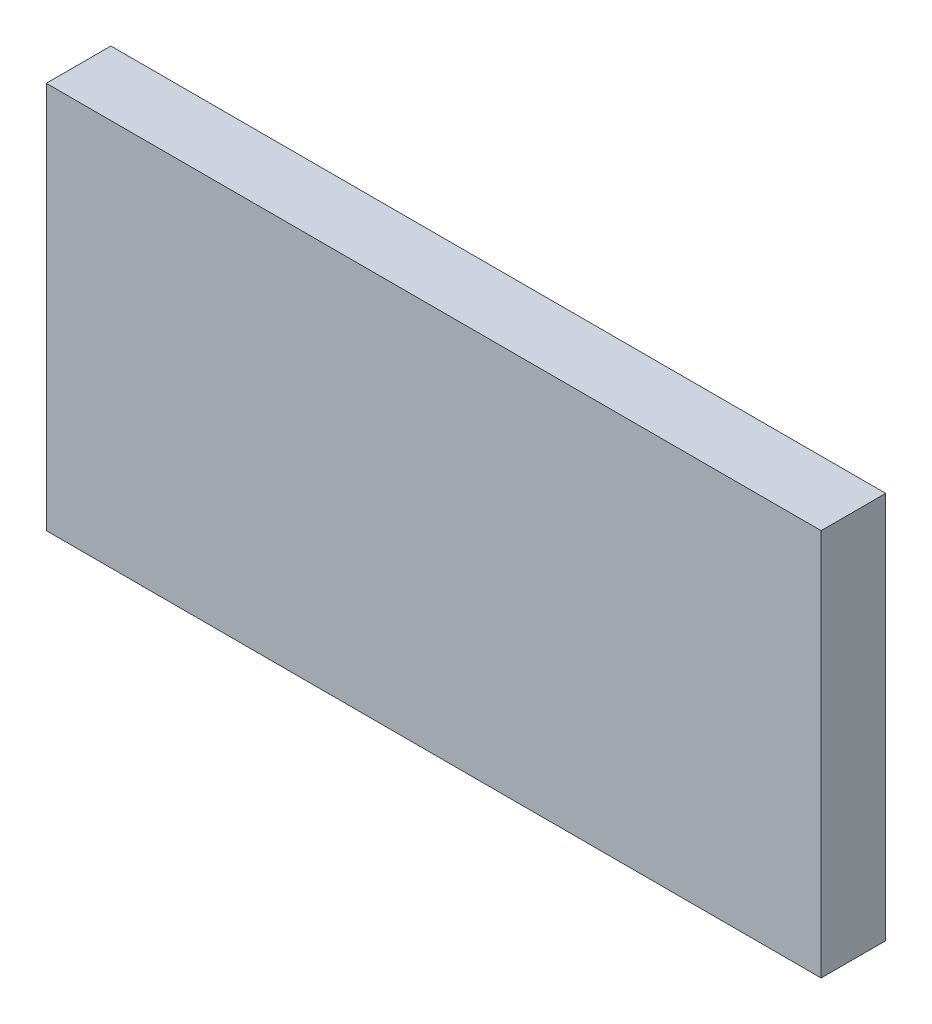
SolidWorks part; units mm, degrees
ref_plane "Plan de face" through (0, 0, 0) normal (0, 0, 1) x (1, 0, 0)
ref_plane "Plan de dessus" through (0, 0, 0) normal (0, 1, 0) x (1, 0, 0)
ref_plane "Plan de droite" through (0, 0, 0) normal (1, 0, 0) x (0, 0, -1)
sketch "Esquisse1" plane through (0, 0, 0) normal (0, 0, 1) x (1, 0, 0)
  line L1 (0, 0) -> (60, 0)
  line L2 (0, 0) -> (0, 30)
  line L3 (0, 30) -> (60, 30)
  line L4 (60, 0) -> (60, 30)
  dimension "D1" = 30
  dimension "D2" = 60
extrude "Boss.-Extru.1" add sketch "Esquisse1" along normal blind 5
